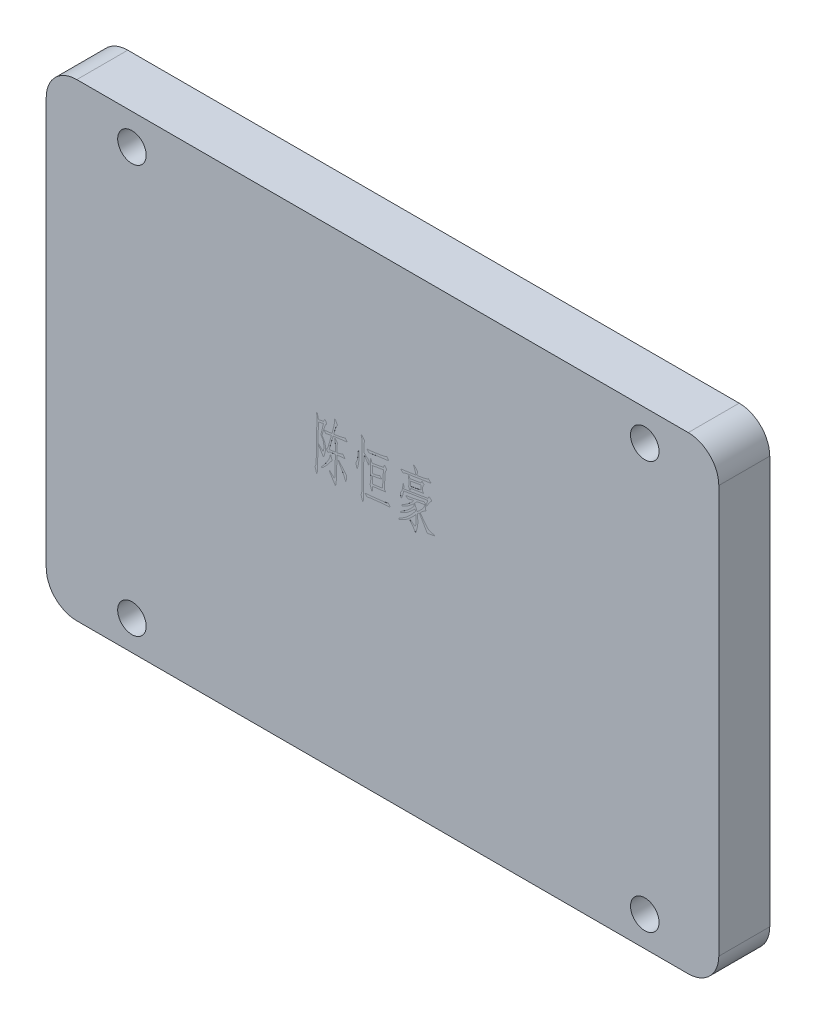
SolidWorks part; units mm, degrees
ref_plane "前视基准面" through (0, 0, 0) normal (0, 0, 1) x (1, 0, 0)
ref_plane "上视基准面" through (0, 0, 0) normal (0, 1, 0) x (1, 0, 0)
ref_plane "右视基准面" through (0, 0, 0) normal (1, 0, 0) x (0, 0, -1)
other "Configuration Table"
sketch "草图2" plane through (0, 0, 0) normal (0, 0, 1) x (1, 0, 0)
  line L1 (15, 0) -> (315, 0)
  line L2 (0, 15) -> (0, 215)
  line L3 (15, 230) -> (315, 230)
  line L4 (330, 15) -> (330, 215)
  arc A0 (15, 0) -> (0, 15) centre (15, 15) cw
  arc A1 (315, 0) -> (330, 15) centre (315, 15) ccw
  arc A2 (315, 230) -> (330, 215) centre (315, 215) cw
  arc A3 (0, 215) -> (15, 230) centre (15, 215) cw
  point P7 (0, 0)
  point P10 (330, 0)
  point P15 (0, 230)
  dimension "D3" = 15
  dimension "D1" = 230
  dimension "D2" = 330
extrude "凸台-拉伸1" add sketch "草图2" along normal blind 25
sketch "草图4" plane through (0, 0, 25) normal (0, 0, 1) x (1, 0, 0)
  line L1 (6.9548, 222.6692) -> (321.9548, 222.6692)
  line L2 (6.9548, 222.6692) -> (6.9548, 7.6692)
  line L3 (6.9548, 7.6692) -> (321.9548, 7.6692)
  line L4 (321.9548, 222.6692) -> (321.9548, 7.6692)
  line L5 (24.7811, 206.8156) -> (304.7811, 206.8156)
  line L6 (24.7811, 206.8156) -> (24.7811, 21.8156)
  line L7 (24.7811, 21.8156) -> (304.7811, 21.8156)
  line L8 (304.7811, 206.8156) -> (304.7811, 21.8156)
  circle A0 centre (42.0495, 214.8391) radius 7
  circle A1 centre (293.6848, 214.8391) radius 7
  circle A2 centre (293.6848, 14.6692) radius 7
  circle A3 centre (42.0495, 14.6692) radius 7
  dimension "D1" = 315
  dimension "D2" = 215
  dimension "D3" = 185
  dimension "D4" = 280
extrude "切除-拉伸5" cut sketch "草图4" against normal up to surface (25 mm away) contours A1 | A2 | A3 | A0 up to face at (165, 115, 0)
sketch "草图5" plane through (0, 0, 25) normal (0, 0, 1) x (1, 0, 0)
  text T0 "陈恒豪" font "汉仪长仿宋体" height 20
extrude "切除-拉伸7" cut sketch "草图5" against normal blind 0.001
